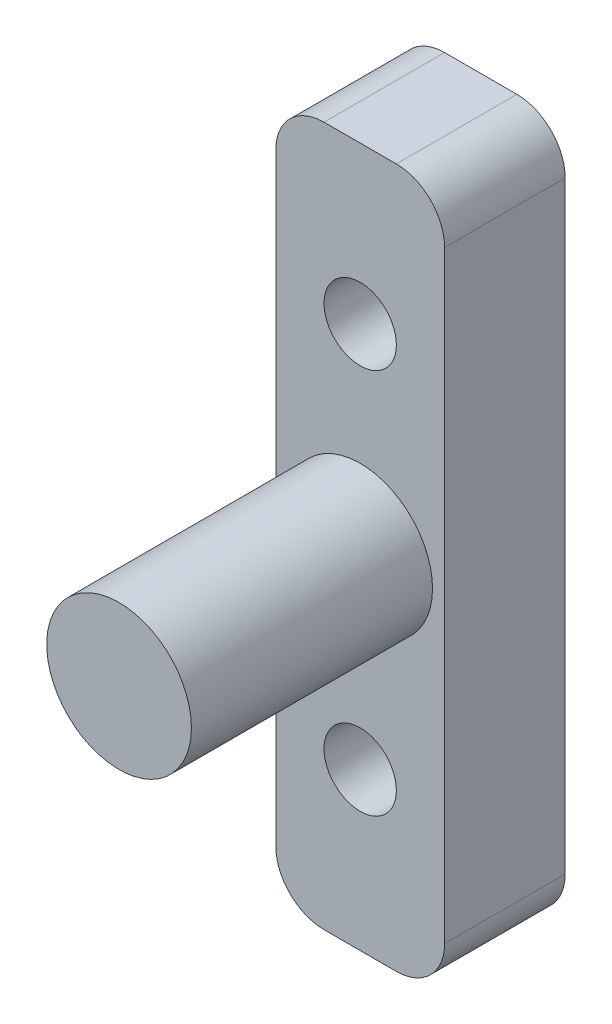
SolidWorks part; units mm, degrees
ref_plane "Front Plane" through (0, 0, 0) normal (0, 0, 1) x (1, 0, 0)
ref_plane "Top Plane" through (0, 0, 0) normal (0, 1, 0) x (1, 0, 0)
ref_plane "Right Plane" through (0, 0, 0) normal (1, 0, 0) x (0, 0, -1)
sketch "Sketch1" plane through (0, 0, 0) normal (0, 0, 1) x (1, 0, 0)
  line L0 (0, -12.5) -> (0, 12.5)
  line L1 (7, -12.5) -> (7, 12.5)
  line L2 (2, 14.5) -> (5, 14.5)
  line L3 (2, -14.5) -> (5, -14.5)
  line L4 (7, -14.5) -> (7, 14.5) construction
  line L5 (0, -14.5) -> (0, 14.5) construction
  arc A0 (7, 12.5) -> (5, 14.5) centre (5, 12.5) ccw
  arc A1 (0, 12.5) -> (2, 14.5) centre (2, 12.5) cw
  arc A2 (0, -12.5) -> (2, -14.5) centre (2, -12.5) ccw
  arc A3 (7, -12.5) -> (5, -14.5) centre (5, -12.5) cw
  point P4 (0, 0)
  point P13 (0, 14.5)
  dimension "D3" = 2
  dimension "D2" = 7
extrude "Boss-Extrude1" add sketch "Sketch1" along normal blind 5
sketch "Sketch2" plane through (0, 0, 5) normal (0, 0, 1) x (1, 0, 0)
  line L0 (3.5, 14.5) -> (3.5, -14.5) construction
  line L1 (5, 14.5) -> (2, 14.5) construction
  line L2 (2, -14.5) -> (5, -14.5) construction
  line L3 (0, 0) -> (8.9626, 0) construction
  circle A0 centre (3.5, 0) radius 3
  dimension "D1" = 6
extrude "Boss-Extrude2" add sketch "Sketch2" along normal blind 10
sketch "Sketch3" plane through (0, 0, 5) normal (0, 0, 1) x (1, 0, 0)
  line L0 (3.5, 0) -> (3.5, -16.7724) construction
  line L1 (3.5, 0) -> (3.5, 15.7337) construction
  circle A0 centre (3.5, 8) radius 1.5
  circle A1 centre (3.5, -8) radius 1.5
  dimension "D1" = 3
  dimension "D2" = 3
  dimension "D3" = 8
  dimension "D4" = 8
extrude "Cut-Extrude1" cut sketch "Sketch3" against normal through all
